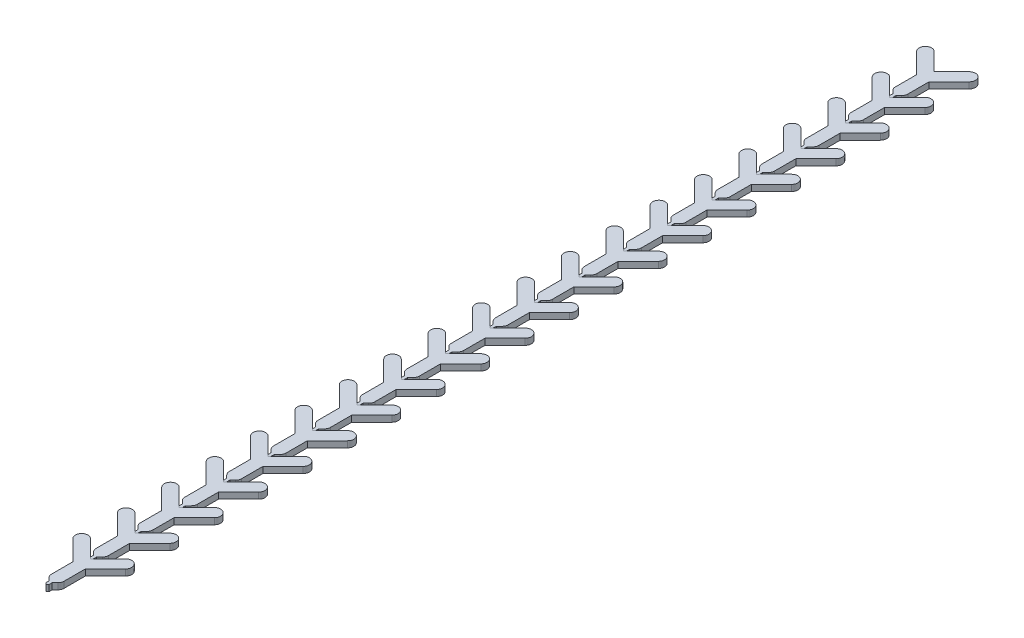
SolidWorks part; units mm, degrees
material "Rubber"
ref_plane "Front Plane" through (0, 0, 0) normal (0, 0, 1) x (1, 0, 0)
ref_plane "Top Plane" through (0, 0, 0) normal (0, 1, 0) x (1, 0, 0)
ref_plane "Right Plane" through (0, 0, 0) normal (1, 0, 0) x (0, 0, -1)
sketch "Sketch1" plane through (0, 0, 0) normal (0, 1, 0) x (1, 0, 0)
  line L0 (0, 0) -> (0, -10) construction
  line L3 (0, 0) -> (7.0711, 7.0711) construction
  line L12 (0, 0) -> (-7.0711, 7.0711) construction
  line L13 (7.0711, 7.0711) -> (8.4853, 5.6569) construction
  line L14 (7.0711, 7.0711) -> (5.6569, 8.4853) construction
  line L15 (-7.0711, 7.0711) -> (-5.6569, 8.4853) construction
  line L17 (-7.0711, 7.0711) -> (-8.4853, 5.6569) construction
  line L19 (0, -10) -> (2, -10) construction
  line L21 (0, -10) -> (-2, -10) construction
  line L27 (-5.6569, 8.4853) -> (0, 2.8284)
  line L28 (0, 2.8284) -> (5.6569, 8.4853)
  line L29 (8.4853, 5.6569) -> (2, -0.8284)
  line L30 (2, -0.8284) -> (2, -7.6716)
  line L31 (-2, -7.6716) -> (-2, -0.8284)
  line L32 (-2, -0.8284) -> (-8.4853, 5.6569)
  line L33 (-0.5, -10) -> (-0.5, -11)
  line L34 (0.5, -10) -> (0.5, -11)
  line L35 (0.5, -11) -> (0, -11.5)
  line L36 (0, -11.5) -> (-0.5, -11)
  line L37 (0.5, -10) -> (1.4142, -9.0858)
  line L38 (-0.5, -10) -> (-1.4142, -9.0858)
  arc A0 (-1.4142, -9.0858) -> (-2, -7.6716) centre (0, -7.6716) cw
  arc A1 (2, -7.6716) -> (1.4142, -9.0858) centre (0, -7.6716) cw
  arc A2 (8.4853, 5.6569) -> (5.6569, 8.4853) centre (7.0711, 7.0711) ccw
  arc A3 (-5.6569, 8.4853) -> (-8.4853, 5.6569) centre (-7.0711, 7.0711) ccw
  dimension "D5" = 2
  dimension "D1" = 1
  dimension "D6" = 0.5
  dimension "D7" = 1
  dimension "D8" = 2
  dimension "D2" = 135
  dimension "D3" = 10
  dimension "D4" = 10
extrude "Boss-Extrude1" add sketch "Sketch1" along normal blind 2
pattern_linear "LPattern2" count 20 spacing 14.32 along (0, 0, 1) of bodies 102
